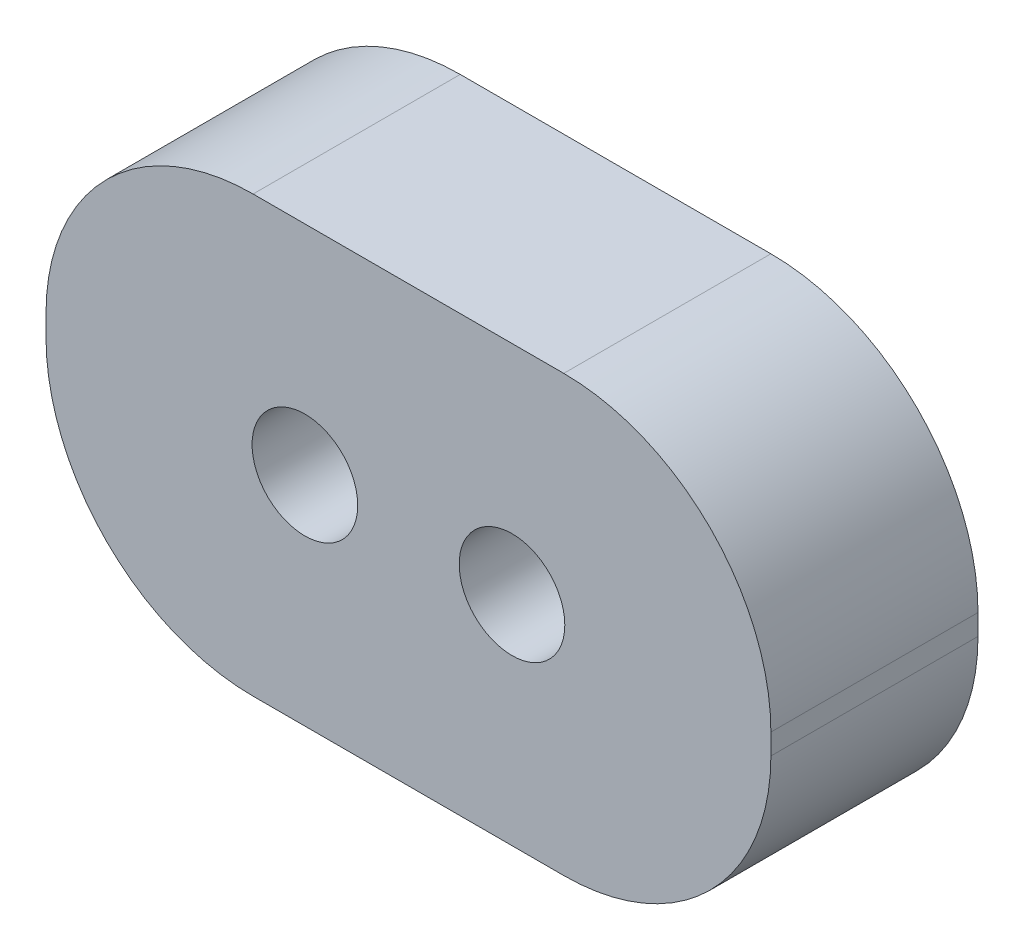
SolidWorks part; units mm, degrees
ref_plane "Płaszczyzna przednia" through (0, 0, 0) normal (0, 0, 1) x (1, 0, 0)
ref_plane "Płaszczyzna górna" through (0, 0, 0) normal (0, 1, 0) x (1, 0, 0)
ref_plane "Płaszczyzna prawa" through (0, 0, 0) normal (1, 0, 0) x (0, 0, -1)
sketch "Szkic1" plane through (0, 0, 0) normal (0, 0, 1) x (1, 0, 0)
  line L0 (-171.0228, 296.7374) -> (-161.0228, 296.7374) construction
  line L1 (-158.5228, 286.2374) -> (-173.5228, 286.2374)
  line L8 (-158.5228, 307.2374) -> (-173.5228, 307.2374)
  line L9 (-183.5228, 297.2374) -> (-183.5228, 296.2374)
  line L11 (-148.5228, 296.2374) -> (-148.5228, 297.2374)
  arc A8 (-148.5228, 297.2374) -> (-158.5228, 307.2374) centre (-158.5228, 297.2374) ccw
  arc A9 (-173.5228, 307.2374) -> (-183.5228, 297.2374) centre (-173.5228, 297.2374) ccw
  circle A14 centre (-171.0228, 296.7374) radius 2.55
  circle A15 centre (-161.0228, 296.7374) radius 2.55
  arc A16 (-148.5228, 296.2374) -> (-158.5228, 286.2374) centre (-158.5228, 296.2374) cw
  arc A17 (-173.5228, 286.2374) -> (-183.5228, 296.2374) centre (-173.5228, 296.2374) cw
extrude "Dodanie-wyciągnięcie1" add sketch "Szkic1" along normal blind 10
